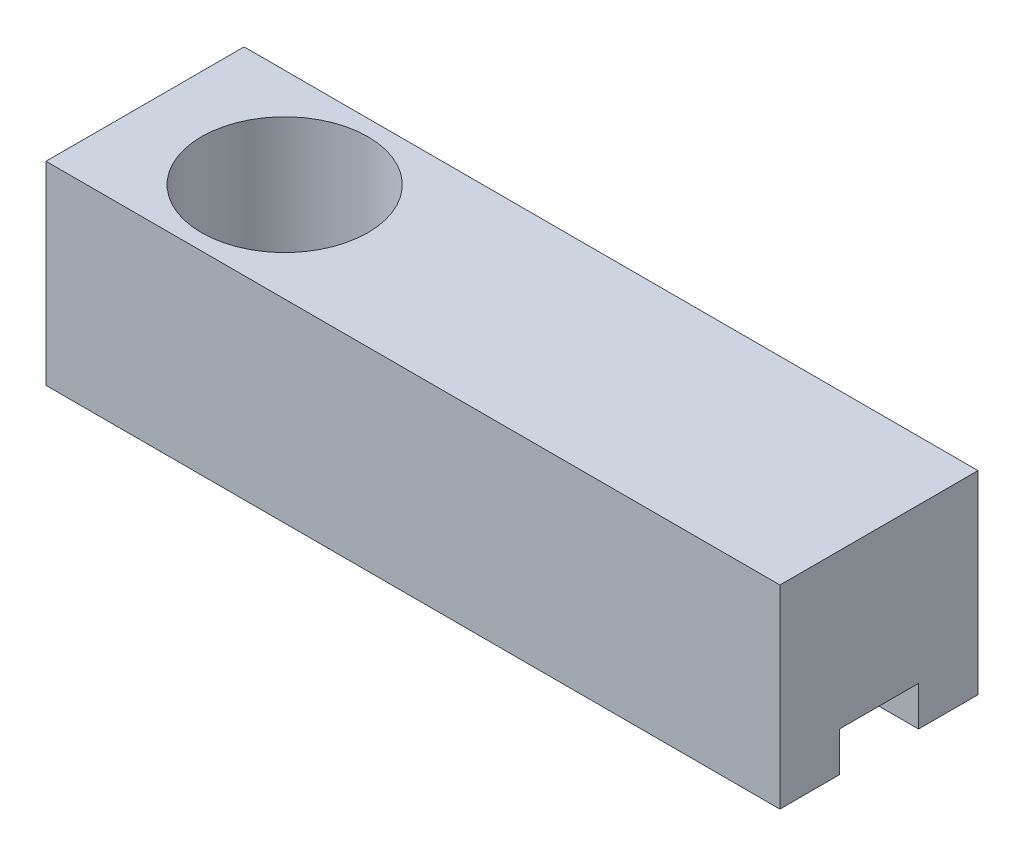
SolidWorks part; units mm, degrees
ref_plane "Front Plane" through (0, 0, 0) normal (0, 0, 1) x (1, 0, 0)
ref_plane "Top Plane" through (0, 0, 0) normal (0, 1, 0) x (1, 0, 0)
ref_plane "Right Plane" through (0, 0, 0) normal (1, 0, 0) x (0, 0, -1)
sketch "Sketch1" plane through (0, 0, 0) normal (0, 1, 0) x (1, 0, 0)
  line L1 (-50, -50) -> (50, -50)
  line L2 (-50, -50) -> (-50, 50)
  line L3 (-50, 50) -> (50, 50)
  line L4 (50, -50) -> (50, 50)
  line L5 (-50, -50) -> (50, 50) construction
  line L6 (-50, 50) -> (50, -50) construction
  point P0 (0, 0)
  dimension "D1" = 100
extrude "Boss-Extrude1" add sketch "Sketch1" along normal blind 50
sketch "Sketch2" plane through (0, 50, 0) normal (0, 1, 0) x (1, 0, 0)
  circle A0 centre (0, 0) radius 21
extrude "Cut-Extrude1" cut sketch "Sketch2" against normal through all
sketch "Sketch3" plane through (50, 0, 0) normal (1, 0, 0) x (0, 0, -1)
  line L0 (-35, 0) -> (35, 0)
  line L1 (-50, 0) -> (50, 0) construction
  line L2 (-35, 0) -> (-35, 50)
  line L3 (-50, 50) -> (50, 50) construction
  line L4 (-35, 50) -> (35, 50)
  line L5 (35, 50) -> (35, 0)
  point P6 (0, 0)
extrude "Boss-Extrude2" add sketch "Sketch3" along normal blind 100
sketch "Sketch4" plane through (-50, 0, 0) normal (-1, 0, 0) x (0, 0, 1)
  line L0 (50, 50) -> (50, 0) construction
  line L1 (-50, 50) -> (50, 50)
  line L2 (-50, 50) -> (-50, 49)
  line L3 (-50, 49) -> (50, 49)
  line L4 (50, 50) -> (50, 49)
extrude "Cut-Extrude2" cut sketch "Sketch4" against normal through all
sketch "Sketch6" plane through (150, 0, 0) normal (1, 0, 0) x (0, 0, -1)
  line L1 (-35, 0) -> (35, 0) construction
  line L3 (-10, 0) -> (10, 0)
  line L4 (-10, 0) -> (-10, 10)
  line L5 (-10, 10) -> (10, 10)
  line L6 (10, 0) -> (10, 10)
  point P5 (0, 0)
extrude "Cut-Extrude3" cut sketch "Sketch6" against normal blind 25
sketch "Sketch7" plane through (0, 10, 0) normal (0, -1, 0) x (1, 0, 0)
  line L0 (125, -10) -> (150, -10) construction
  line L1 (125, 10) -> (135, 10)
  line L2 (125, 10) -> (125, -10)
  line L3 (125, -10) -> (135, -10)
  line L4 (135, 10) -> (135, -10)
  dimension "D1" = 10
extrude "Cut-Extrude4" cut sketch "Sketch7" against normal blind 10
sketch "Sketch8" plane through (50, 0, 0) normal (1, 0, 0) x (0, 0, -1)
  line L1 (35, 49) -> (50, 49)
  line L2 (35, 49) -> (35, 0)
  line L3 (35, 0) -> (50, 0)
  line L4 (50, 49) -> (50, 0)
  line L5 (-35, 49) -> (-50, 49)
  line L6 (-35, 49) -> (-35, 0)
  line L7 (-35, 0) -> (-50, 0)
  line L8 (-50, 49) -> (-50, 0)
extrude "Cut-Extrude5" cut sketch "Sketch8" against normal through all
sketch "Sketch9" plane through (0, 49, 0) normal (0, 1, 0) x (1, 0, 0)
  line L0 (150, -35) -> (-50, -35) construction
  line L1 (-50, 35) -> (-35.2446, 35)
  line L2 (-50, 35) -> (-50, -35)
  line L3 (-50, -35) -> (-35.2446, -35)
  line L4 (-35.2446, 35) -> (-35.2446, -35)
extrude "Cut-Extrude6" cut sketch "Sketch9" against normal through all
sketch "Sketch10" plane through (-35.2446, 0, 0) normal (-1, 0, 0) x (0, 0, 1)
  line L0 (35, 0) -> (-35, 0) construction
  line L1 (-35, 49) -> (-25, 49)
  line L2 (-35, 49) -> (-35, 0)
  line L3 (-35, 0) -> (-25, 0)
  line L4 (-25, 49) -> (-25, 0)
  line L6 (35, 49) -> (25, 49)
  line L7 (35, 49) -> (35, 0)
  line L8 (35, 0) -> (25, 0)
  line L9 (25, 49) -> (25, 0)
extrude "Cut-Extrude7" cut sketch "Sketch10" against normal through all
